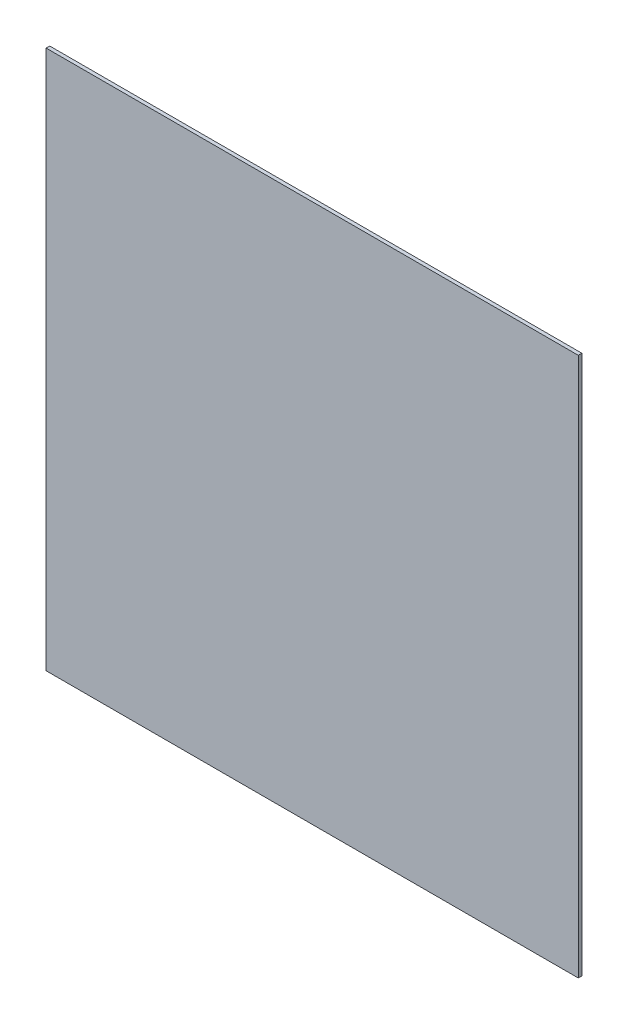
SolidWorks part; units mm, degrees
material "Perspex (TM) GS Acrylic Cast Sheet"
ref_plane "Front Plane" through (0, 0, 0) normal (0, 0, 1) x (1, 0, 0)
ref_plane "Top Plane" through (0, 0, 0) normal (0, 1, 0) x (1, 0, 0)
ref_plane "Right Plane" through (0, 0, 0) normal (1, 0, 0) x (0, 0, -1)
sketch "Sketch1" plane through (0, 0, 0) normal (0, 0, 1) x (1, 0, 0)
  line L1 (0, 0) -> (444, 0)
  line L2 (0, 0) -> (0, 450)
  line L3 (0, 450) -> (444, 450)
  line L4 (444, 0) -> (444, 450)
  dimension "D1" = 444
  dimension "D2" = 450
extrude "Boss-Extrude1" add sketch "Sketch1" along normal blind 3
